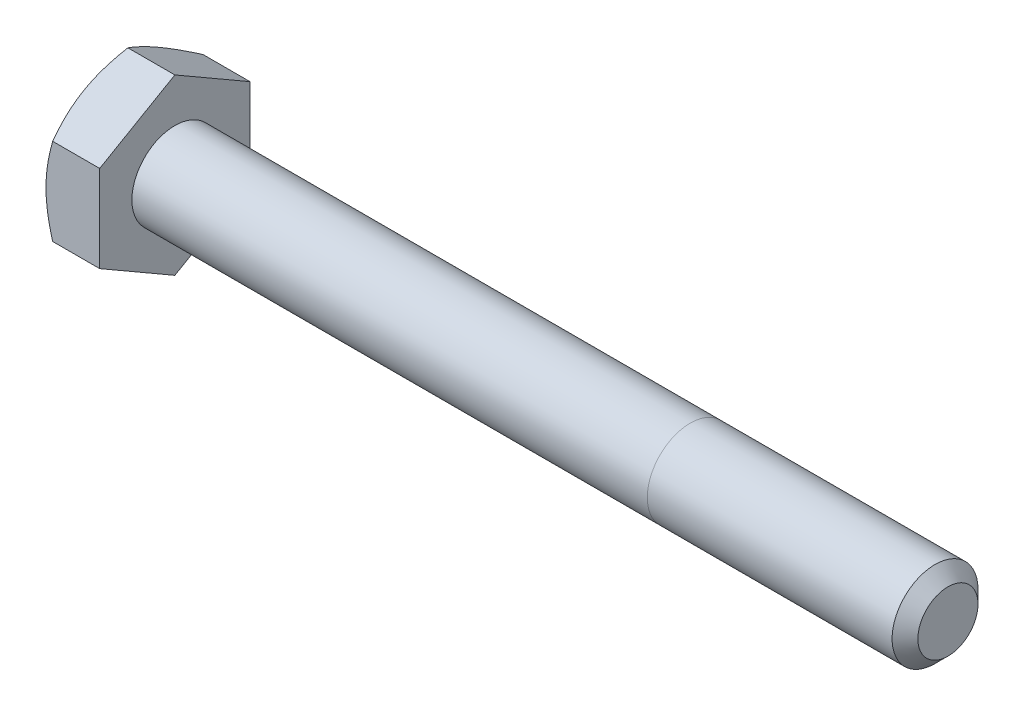
SolidWorks part; units mm, degrees
material "Alloy Steel"
ref_plane "Front Plane" through (0, 0, 0) normal (0, 0, 1) x (1, 0, 0)
ref_plane "Top Plane" through (0, 0, 0) normal (0, 1, 0) x (1, 0, 0)
ref_plane "Right Plane" through (0, 0, 0) normal (1, 0, 0) x (0, 0, -1)
sketch "Sketch1" plane through (0, 0, 0) normal (0, 0, 1) x (1, 0, 0)
  line L0 (-30.5594, 0) -> (30.5594, 0) construction
  line L1 (30.5594, 3.175) -> (30.5594, -3.175) construction
  line L2 (-26.5906, 5.5562) -> (-26.5906, -5.5562) construction
  line L3 (-30.5594, 5.5562) -> (-30.5594, -5.5562) construction
  point P9 (-26.5906, 0)
  point P10 (26.1144, -3.175)
  dimension "D1" = 4.445
  dimension "Screw Dia" = 6.35
  dimension "Hex" = 11.1125
  dimension "Head Ht" = 3.9688
  dimension "Screw Lenght" = 57.15
ref_plane "Plane2" through (30.5594, 0, 0) normal (1, 0, 0) x (0, 0, -1)
sketch "Sketch5" plane through (30.5594, 0, 0) normal (1, 0, 0) x (0, 0, -1)
  circle A0 centre (0, 0) radius 3.175
extrude "Boss-Extrude3" add sketch "Sketch5" against normal up to vertex (57.15 mm away) up to point (-26.5906, 0, 0)
sketch "Sketch9" plane through (30.5594, 0, 0) normal (1, 0, 0) x (0, 0, -1)
  circle A1 centre (0, 0) radius 3.175
  circle A2 centre (0, 0) radius 3.175
  dimension "D1" = 0
curve "Helix/Spiral1" pitch 1.27 height 20.32 turns 16 parameters "Pitch"=1.27
chamfer "Chamfer1" distance 0.9525 angle 45 1 edges at (30.5594, 0, -3.175)
sketch "Sketch10" plane through (0, 0, 0) normal (0, 0, 1) x (1, 0, 0)
  line L0 (30.5594, 3.175) -> (31.0356, 2.3501)
  line L1 (31.0356, 2.3501) -> (31.1944, 2.3501)
  line L2 (31.1944, 2.3501) -> (31.6706, 3.175)
  line L3 (30.5594, 3.175) -> (31.6706, 3.175)
  line L4 (31.115, 3.175) -> (31.115, 2.3501) construction
  line L5 (30.7975, 2.7626) -> (31.4325, 2.7626) construction
  dimension "D1" = 60
  dimension "D2" = 0.1588
  dimension "D3" = 0.635
sketch "Sketch11" plane through (0, 0, 0) normal (0, 0, 1) x (1, 0, 0)
  line L0 (-26.5906, 3.175) -> (-26.5906, 0)
  line L1 (-26.5906, 0) -> (14.6844, 0)
  line L3 (14.6844, 0) -> (11.5094, 3.175)
  line L4 (-26.5906, 3.175) -> (11.5094, 3.175)
  dimension "D1" = 45
  dimension "MIn Thread" = 19.05
revolve "Revolve1" add sketch "Sketch11" angle 360 about L1
sketch "Sketch6" plane through (-26.5906, 0, 0) normal (-1, 0, 0) x (0, 0, 1)
  line L0 (0, 5.5562) -> (0, -5.5562) construction
  line L1 (5.5563, 3.2079) -> (0, 6.4158)
  line L2 (0, 6.4158) -> (-5.5562, 3.2079)
  line L3 (-5.5562, 3.2079) -> (-5.5562, -3.2079)
  line L4 (-5.5562, -3.2079) -> (0, -6.4158)
  line L5 (0, -6.4158) -> (5.5563, -3.2079)
  line L6 (5.5563, -3.2079) -> (5.5563, 3.2079)
  circle A0 centre (0, 0) radius 5.5563 construction
extrude "Boss-Extrude4" add sketch "Sketch6" along normal up to vertex (3.9688 mm away) up to point (-30.5594, -5.5562, 0)
sketch "Sketch7" plane through (-30.5594, 0, 0) normal (-1, 0, 0) x (0, 0, 1)
  circle A0 centre (0, 0) radius 5.5563 construction
  circle A1 centre (0, 0) radius 5.5563
sketch "Sketch8" plane through (-30.5594, 0, 0) normal (-1, 0, 0) x (0, 0, 1)
  circle A0 centre (0, 0) radius 5.5563 construction
  circle A1 centre (0, 0) radius 5.5563
extrude "Cut-Extrude3" cut sketch "Sketch8" against normal through all draft 60 flip side to cut
sketch "Sketch12" plane through (-30.5594, 0, 0) normal (-1, 0, 0) x (0, 0, 1)
  line L0 (0, 4.2783) -> (0, 2.3892) construction
  line L1 (0.1667, 4.2783) -> (0.1667, 2.3892)
  line L2 (-0.1667, 4.2783) -> (-0.1667, 2.3892)
  line L3 (0, 3.175) -> (0, -3.175) construction
  arc A0 (0.1667, 4.2783) -> (-0.1667, 4.2783) centre (0, 4.2783) ccw
  arc A1 (-0.1667, 2.3892) -> (0.1667, 2.3892) centre (0, 2.3892) ccw
  circle A3 centre (0, 0) radius 2.2225 construction
  circle A4 centre (0, 0) radius 4.445 construction
  point P2 (0, 3.3337)
  dimension "D1" = 4.445
  dimension "D3" = 8.89
  dimension "D2" = 0.3334
extrude "Cut-Extrude4" cut sketch "Sketch12" against normal blind 0.254
pattern_circular "CirPattern1" count 3 over 360 about axis through (0, 0, 0) along (1, 0, 0) of "Cut-Extrude4"
sketch "Sketch13" plane through (0, 0, 0) normal (0, 1, 0) x (1, 0, 0)
  line L0 (11.5094, 3.175) -> (11.5094, -3.175)
  line L3 (30.5594, -2.2225) -> (30.5594, 2.2225) construction
  line L4 (29.6069, 3.175) -> (-26.5906, 3.175) construction
  line L5 (-26.5906, -3.175) -> (29.6069, -3.175) construction
  point P2 (11.5094, 3.175)
  point P5 (11.5094, -3.175)
  point P6 (11.5094, 0)
  point P11 (11.5094, 0)
  dimension "D1" = 19.05
split line "Split Line1"
equation "\"D2@Sketch10\" = \"Pitch@Helix/Spiral1\"*.125"
equation "\"D3@Sketch10\" = \"Pitch@Helix/Spiral1\"*.5"
equation "\"D3@Helix/Spiral1\" = \"MIn Thread@Sketch11\"+\"Pitch@Helix/Spiral1\""
equation "\"D1@Chamfer1\" = \"Pitch@Helix/Spiral1\"*.75"
equation "\"D1@Sketch12\" = \"Hex@Sketch1\"*.4"
equation "\"D3@Sketch12\" = \"Hex@Sketch1\"*.8"
equation "\"D2@Sketch12\" = \"Hex@Sketch1\"*.03"
equation "\"D1@Sketch1\" = \"Pitch@Helix/Spiral1\"*3.5"
